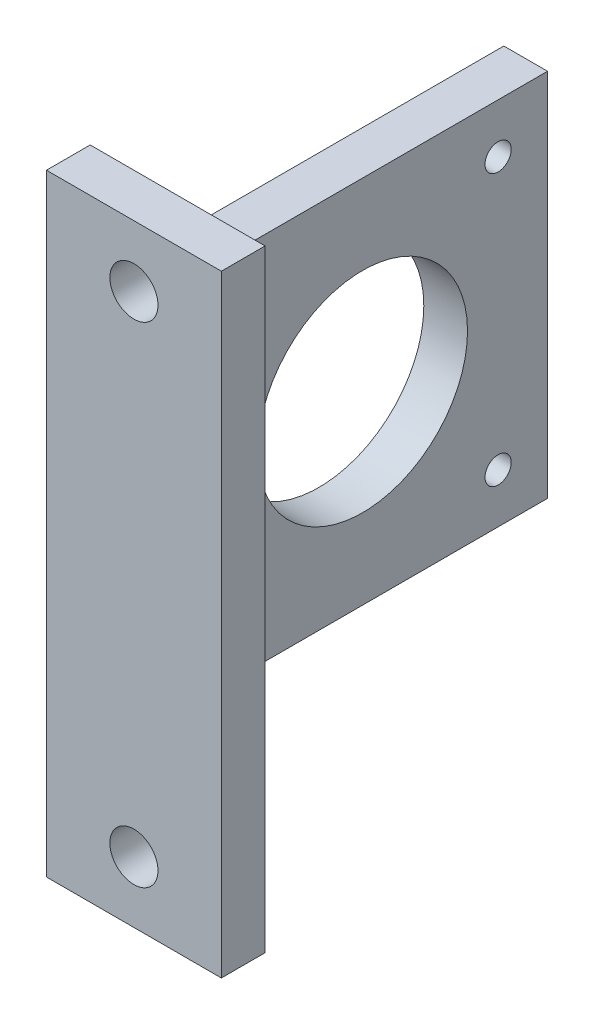
SolidWorks part; units mm, degrees
ref_plane "Front Plane" through (0, 0, 0) normal (0, 0, 1) x (1, 0, 0)
ref_plane "Top Plane" through (0, 0, 0) normal (0, 1, 0) x (1, 0, 0)
ref_plane "Right Plane" through (0, 0, 0) normal (1, 0, 0) x (0, 0, -1)
sketch "Sketch2" plane through (0, 0, 0) normal (1, 0, 0) x (0, 0, -1)
  line L1 (-21.15, 21.15) -> (21.15, 21.15)
  line L2 (-21.15, 21.15) -> (-21.15, -21.15)
  line L3 (-21.15, -21.15) -> (21.15, -21.15)
  line L4 (21.15, 21.15) -> (21.15, -21.15)
  line L5 (-21.15, 21.15) -> (21.15, -21.15) construction
  line L6 (-21.15, -21.15) -> (21.15, 21.15) construction
  circle A0 centre (-15.5, 15.5) radius 1.5
  circle A1 centre (15.5, 15.5) radius 1.5
  circle A2 centre (15.5, -15.5) radius 1.5
  circle A3 centre (-15.5, -15.5) radius 1.5
  circle A4 centre (0, 0) radius 12
  point P0 (0, 0)
  dimension "D7" = 3
  dimension "D8" = 24
  dimension "D1" = 42.3
  dimension "D2" = 42.3
  dimension "D3" = 15.5
  dimension "D4" = 31
  dimension "D5" = 31
  dimension "D6" = 31
extrude "Boss-Extrude1" add sketch "Sketch2" along normal blind 5
sketch "Sketch5" plane through (0, 0, 21.15) normal (0, 0, 1) x (1, 0, 0)
  line L1 (0, 21.15) -> (5, 21.15)
  line L2 (0, 21.15) -> (0, -21.15)
  line L3 (0, -21.15) -> (5, -21.15)
  line L4 (5, 21.15) -> (5, -21.15)
extrude "Boss-Extrude3" add sketch "Sketch5" along normal blind 5
sketch "Sketch3" plane through (0, 0, 26.15) normal (0, 0, 1) x (1, 0, 0)
  line L1 (0, 35) -> (0, -35)
  line L2 (0, -35) -> (20, -35)
  line L3 (20, -35) -> (20, 35)
  line L4 (20, 35) -> (0, 35)
  circle A0 centre (10, 28) radius 2.75
  circle A1 centre (10, -28) radius 2.75
  dimension "D1" = 5.5
  dimension "D2" = 7
  dimension "D3" = 10
  dimension "D4" = 7
  dimension "D5" = 10
  dimension "D6" = 70
  dimension "D7" = 35
  dimension "D8" = 20
extrude "Boss-Extrude2" add sketch "Sketch3" along normal blind 5
fillet "Fillet1" radius 4 2 edges at (2.5, -21.15, 26.15) (2.5, 21.15, 26.15)
